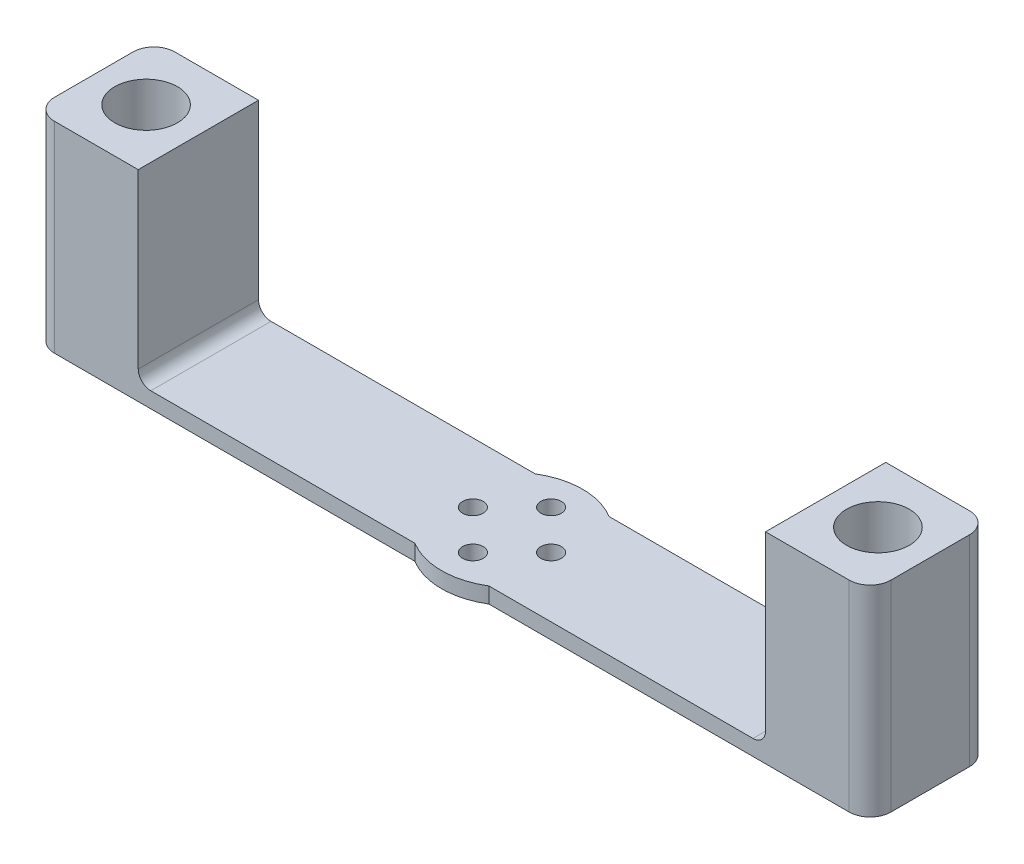
SolidWorks part; units mm, degrees
ref_plane "Front Plane" through (0, 0, 0) normal (0, 0, 1) x (1, 0, 0)
ref_plane "Top Plane" through (0, 0, 0) normal (0, 1, 0) x (1, 0, 0)
ref_plane "Right Plane" through (0, 0, 0) normal (1, 0, 0) x (0, 0, -1)
sketch "Sketch1" plane through (0, 0, 0) normal (0, 1, 0) x (1, 0, 0)
  line L0 (0, 0) -> (0, 4.9523) construction
  line L1 (0, 4.9523) -> (0, 0) construction
  line L2 (0, 0) -> (2.8355, 0) construction
  circle A0 centre (0, 0) radius 17.145
  circle A2 centre (0, 9.5) radius 2.5
  circle A3 centre (9.5, 0) radius 2.5
  circle A4 centre (0, -9.5) radius 2.5
  circle A5 centre (-9.5, 0) radius 2.5
  dimension "D2" = 34.29
  dimension "D3" = 5
extrude "Boss-Extrude1" add sketch "Sketch1" along normal blind 3.81
sketch "Sketch2" plane through (0, 3.81, 0) normal (0, 1, 0) x (1, 0, 0)
  line L1 (-96.52, -14.605) -> (96.52, -14.605)
  line L2 (-101.6, -9.525) -> (-101.6, 9.525)
  line L3 (-96.52, 14.605) -> (96.52, 14.605)
  line L4 (101.6, -9.525) -> (101.6, 9.525)
  line L5 (-101.6, -14.605) -> (101.6, 14.605) construction
  line L6 (-101.6, 14.605) -> (101.6, -14.605) construction
  circle A0 centre (-88.9, 0) radius 7.62
  circle A1 centre (88.9, 0) radius 7.62
  arc A3 (96.52, 14.605) -> (101.6, 9.525) centre (96.52, 9.525) cw
  arc A4 (96.52, -14.605) -> (101.6, -9.525) centre (96.52, -9.525) ccw
  arc A5 (-96.52, -14.605) -> (-101.6, -9.525) centre (-96.52, -9.525) cw
  arc A6 (-101.6, 9.525) -> (-96.52, 14.605) centre (-96.52, 9.525) cw
  circle A7 centre (9.5, 0) radius 2.5 construction
  circle A8 centre (0, 9.5) radius 2.5 construction
  circle A9 centre (-9.5, 0) radius 2.5 construction
  circle A10 centre (0, -9.5) radius 2.5 construction
  circle A11 centre (9.5, 0) radius 2.5
  circle A12 centre (0, 9.5) radius 2.5
  circle A13 centre (-9.5, 0) radius 2.5
  circle A14 centre (0, -9.5) radius 2.5
  point P0 (0, 0)
  dimension "D2" = 15.24
  dimension "D3" = 15.24
  dimension "D8" = 5.08
  dimension "D1" = 29.21
  dimension "D4" = 88.9
  dimension "D6" = 12.7
  dimension "D7" = 12.7
extrude "Boss-Extrude2" add sketch "Sketch2" along normal blind 45 and the other way through all
sketch "Sketch5" plane through (0, 0, -14.605) normal (0, 0, -1) x (-1, 0, 0)
  line L0 (-101.6, 0) -> (-101.6, 48.81)
  line L1 (-101.6, 48.81) -> (-76.2, 48.81)
  line L2 (-96.52, 48.81) -> (96.52, 48.81) construction
  line L3 (-76.2, 48.81) -> (-76.2, 3.81)
  line L4 (-76.2, 3.81) -> (76.2, 3.81)
  line L5 (0, 3.81) -> (0, 0)
  line L6 (101.6, 0) -> (-101.6, 0)
  line L7 (76.2, 48.81) -> (76.2, 3.81)
  line L8 (101.6, 48.81) -> (76.2, 48.81)
  line L9 (101.6, 0) -> (101.6, 48.81)
  line M8 (96.52, 48.81) -> (-96.52, 48.81)
  dimension "D1" = 25.4
  dimension "D2" = 3.81
extrude "Cut-Extrude2" cut sketch "Sketch5" against normal through all contours L7 L3 L4 M8
sketch "Sketch6" plane through (0, 0, 0) normal (0, -1, 0) x (1, 0, 0)
  circle A0 centre (-88.9, 0) radius 8.89
  circle A1 centre (-88.9, 0) radius 4.445
  circle A2 centre (88.9, 0) radius 8.89
  circle A3 centre (88.9, 0) radius 4.445
  dimension "D1" = 8.89
  dimension "D2" = 8.89
extrude "Boss-Extrude3" add sketch "Sketch6" against normal blind 4.572
fillet "Fillet2" radius 3.048 2 edges at (76.2, 3.81, 0) (-76.2, 3.81, 0)
